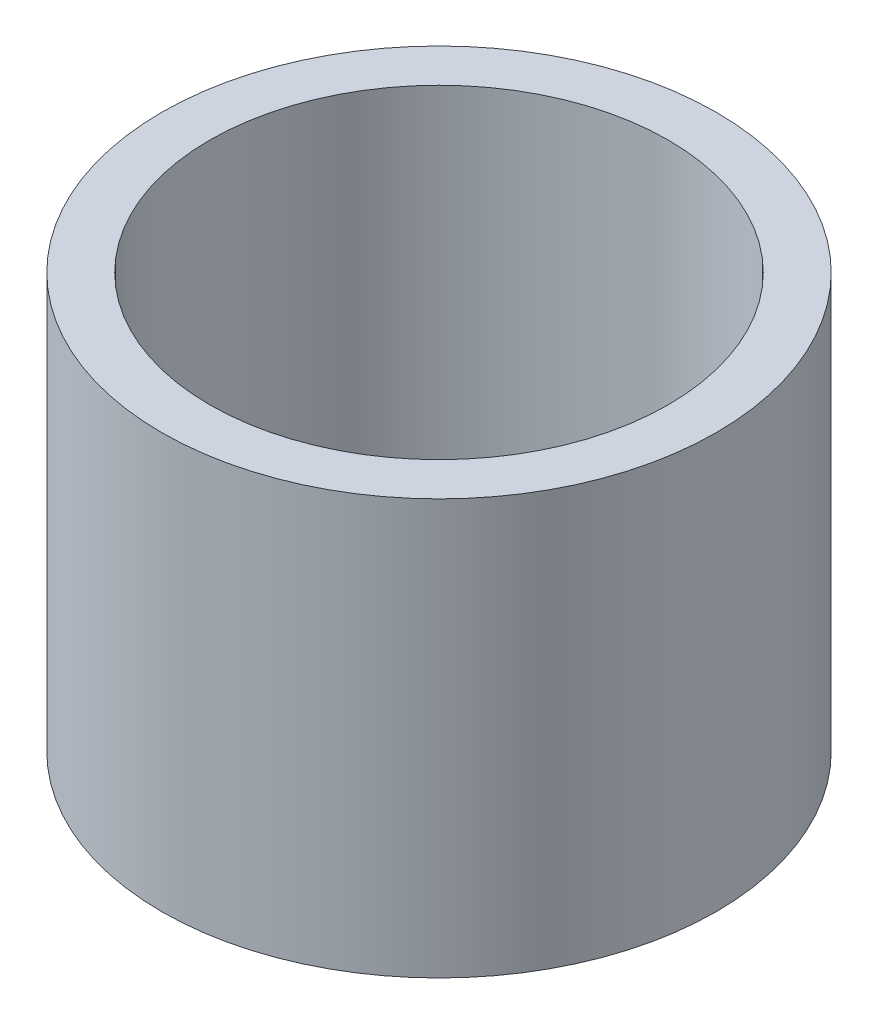
SolidWorks part; units mm, degrees
material "PETG"
ref_plane "Спереди" through (0, 0, 0) normal (0, 0, 1) x (1, 0, 0)
ref_plane "Сверху" through (0, 0, 0) normal (0, 1, 0) x (1, 0, 0)
ref_plane "Справа" through (0, 0, 0) normal (1, 0, 0) x (0, 0, -1)
sketch "Эскиз1" plane through (0, 0, 0) normal (0, 1, 0) x (1, 0, 0)
  circle A0 centre (0, 0) radius 5.25
  circle A1 centre (0, 0) radius 6.35
  dimension "D1" = 12.7
  dimension "D2" = 10.5
extrude "Бобышка-Вытянуть1" add sketch "Эскиз1" along normal blind 9.5
